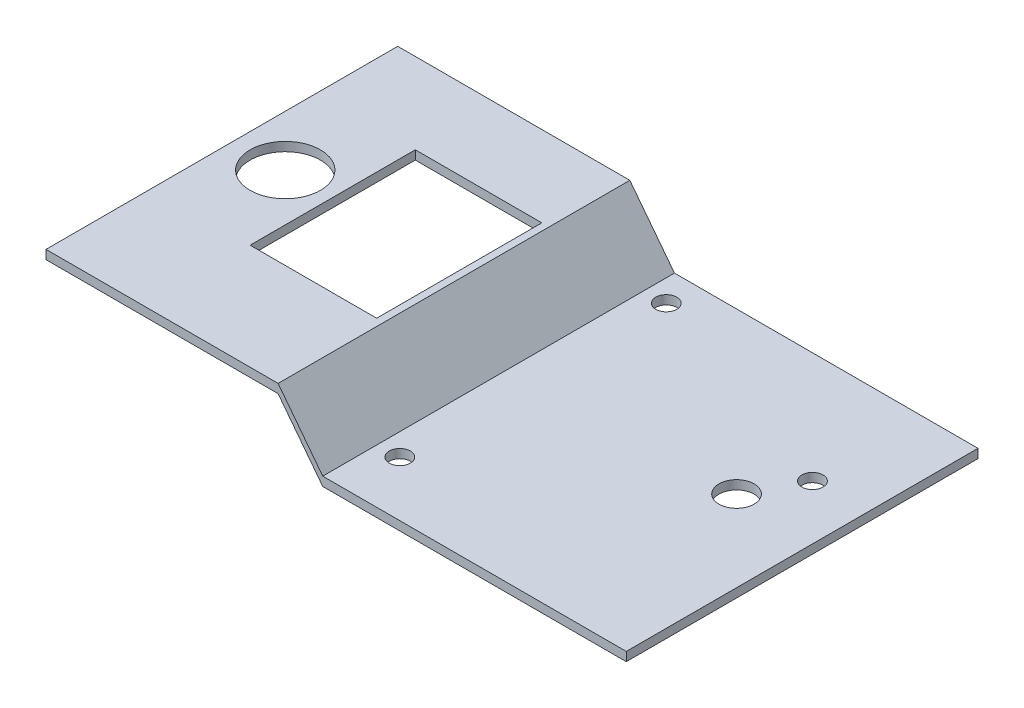
SolidWorks part; units mm, degrees
ref_plane "Front Plane" through (0, 0, 0) normal (0, 0, 1) x (1, 0, 0)
ref_plane "Top Plane" through (0, 0, 0) normal (0, 1, 0) x (1, 0, 0)
ref_plane "Right Plane" through (0, 0, 0) normal (1, 0, 0) x (0, 0, -1)
sketch "Sketch1" plane through (0, 0, 0) normal (0, 0, 1) x (1, 0, 0)
  line L0 (0, 0) -> (0, 2.54)
  line L1 (0, 2.54) -> (66.04, 2.54)
  line L2 (0, 0) -> (66.04, 0)
  line L3 (66.04, 0) -> (66.04, -16.51)
  line L4 (66.04, -16.51) -> (78.74, -16.51)
  line L5 (66.04, 0) -> (78.74, -16.51)
  line L6 (78.74, -16.51) -> (165.1, -16.51)
  line L7 (165.1, -16.51) -> (165.1, -13.97)
  line L8 (165.1, -13.97) -> (78.74, -13.97)
  line L9 (78.74, -13.97) -> (66.04, 2.54)
  dimension "D1" = 66.04
  dimension "D2" = 2.54
  dimension "D3" = 16.51
  dimension "D4" = 12.7
  dimension "D5" = 86.36
  dimension "D6" = 2.54
extrude "Boss-Extrude1" add sketch "Sketch1" against normal blind 1.016 and the other way blind 99.06 contours L8 L9 L1 L0 L2 L5 L6 L7
sketch "Sketch2" plane through (0, 2.54, 0) normal (0, 1, 0) x (1, 0, 0)
  line L0 (-88.9617, -45.484) -> (180.9617, -45.484) construction
  line L1 (28, -68.984) -> (64, -68.984)
  line L2 (28, -68.984) -> (28, -21.984)
  line L3 (28, -21.984) -> (64, -21.984)
  line L4 (64, -68.984) -> (64, -21.984)
  line L5 (28, -68.984) -> (64, -21.984) construction
  line L6 (28, -21.984) -> (64, -68.984) construction
  line L7 (0, 1.016) -> (66.04, 1.016) construction
  line L8 (0, -99.06) -> (0, 1.016) construction
  line L10 (165.1, 1.016) -> (78.74, 1.016) construction
  circle A0 centre (85, -7.584) radius 3
  circle A1 centre (85, -83.384) radius 3
  circle A2 centre (149.6, -30.584) radius 3
  circle A3 centre (14.5, -45.484) radius 10
  circle A4 centre (142, -44.584) radius 5
  point P0 (46, -45.484)
  point P17 (46, -45.484)
  point P22 (28, -45.484)
  point P25 (64, -45.484)
  point P26 (0, 0)
  point P27 (0, 0)
  point P28 (121.4335, -45.484)
  point P29 (0, 0)
  point P30 (0, 0)
  point P31 (0, 0)
  dimension "D6" = 6
  dimension "D8" = 31.6
  dimension "D10" = 6
  dimension "D12" = 13.5
  dimension "D13" = 20
  dimension "D16" = 10
  dimension "D1" = 36
  dimension "D2" = 47
  dimension "D3" = 23
  dimension "D4" = 28
  dimension "D5" = 85
  dimension "D7" = 8.6
  dimension "D9" = 85.6
  dimension "D11" = 0
  dimension "D14" = 14
  dimension "D15" = 78
extrude "Cut-Extrude1" cut sketch "Sketch2" against normal through all
